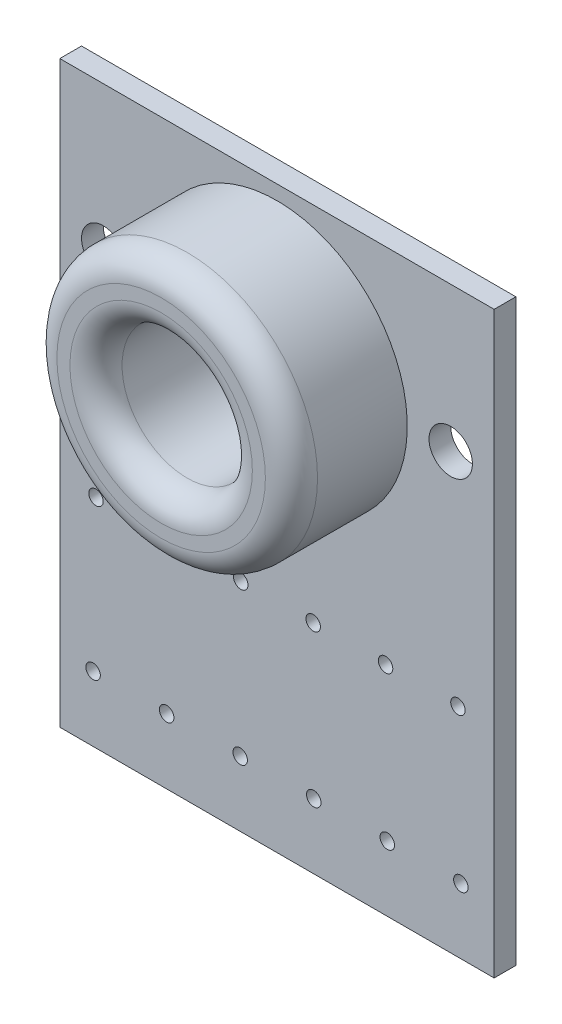
SolidWorks part; units mm, degrees
ref_plane "Спереди" through (0, 0, 0) normal (0, 0, 1) x (1, 0, 0)
ref_plane "Сверху" through (0, 0, 0) normal (0, 1, 0) x (1, 0, 0)
ref_plane "Справа" through (0, 0, 0) normal (1, 0, 0) x (0, 0, -1)
sketch "Эскиз1" plane through (0, 0, 0) normal (0, 0, 1) x (1, 0, 0)
  line L0 (0, 0) -> (0, 36.3379) construction
  line L1 (0, 0) -> (39.357, 0) construction
  line L2 (0, 10) -> (-12.7, 10) construction
  line L3 (-15, -20) -> (15, -20)
  line L4 (-15, -20) -> (-15, 20)
  line L5 (-15, 20) -> (15, 20)
  line L6 (15, -20) -> (15, 20)
  circle A0 centre (-12.7, -15.5) radius 0.5
  circle A1 centre (-12.5, -5) radius 0.5
  circle A2 centre (-7.62, -15.5) radius 0.5
  circle A3 centre (-2.54, -15.5) radius 0.5
  circle A4 centre (2.54, -15.5) radius 0.5
  circle A5 centre (7.62, -15.5) radius 0.5
  circle A6 centre (12.7, -15.5) radius 0.5
  circle A7 centre (-7.5, -5) radius 0.5
  circle A8 centre (-2.5, -5) radius 0.5
  circle A9 centre (2.5, -5) radius 0.5
  circle A10 centre (7.5, -5) radius 0.5
  circle A11 centre (12.5, -5) radius 0.5
  circle A12 centre (0, 10) radius 2
  circle A13 centre (-12, 10) radius 1.5
  circle A14 centre (12, 10) radius 1.5
  dimension "D5" = 1
  dimension "D8" = 1
  dimension "D9" = 4
  dimension "D12" = 3
  dimension "D1" = 30
  dimension "D2" = 40
  dimension "D3" = 4.5
  dimension "D4" = 2.3
  dimension "D6" = 15
  dimension "D7" = 2.5
  dimension "D10" = 30
  dimension "D11" = 3
extrude "Вытянуть1" add sketch "Эскиз1" along normal blind 1.5
sketch "Эскиз2" plane through (0, 0, 1.5) normal (0, 0, 1) x (1, 0, 0)
  circle A0 centre (0, 10) radius 4.5
  circle A1 centre (0, 10) radius 9
  dimension "D1" = 9
  dimension "D2" = 18
extrude "Вытянуть2" add sketch "Эскиз2" along normal blind 8
fillet "Скругление1" radius 1.8 2 edges at (4.5, 10, 9.5) (9, 10, 9.5)
